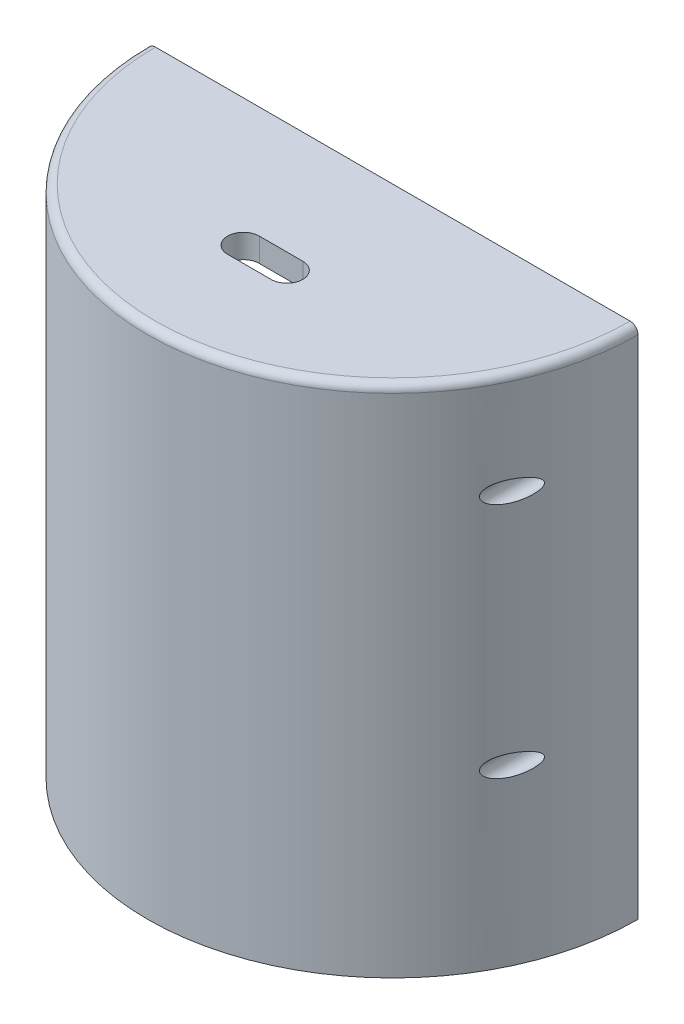
SolidWorks part; units mm, degrees
material "ABS"
ref_plane "Спереди" through (0, 0, 0) normal (0, 0, 1) x (1, 0, 0)
ref_plane "Сверху" through (0, 0, 0) normal (0, 1, 0) x (1, 0, 0)
ref_plane "Справа" through (0, 0, 0) normal (1, 0, 0) x (0, 0, -1)
sketch "Эскиз1" plane through (0, 0, 0) normal (0, 1, 0) x (1, 0, 0)
  line L0 (-31, 0) -> (-28, 0)
  line L1 (28, 0) -> (31, 0)
  arc A2 (31, 0) -> (-31, 0) centre (0, 0) cw
  arc A3 (28, 0) -> (-28, 0) centre (0, 0) cw
  dimension "D1" = 28
  dimension "D2" = 31
extrude "Бобышка-Вытянуть1" add sketch "Эскиз1" along normal blind 65
sketch "Эскиз2" plane through (0, 65, 0) normal (0, 1, 0) x (1, 0, 0)
  line L0 (-31, 0) -> (31, 0)
  arc A3 (31, 0) -> (-31, 0) centre (0, 0) cw
  arc A4 (-31, 0) -> (31, 0) centre (0, 0) ccw construction
sketch "Эскиз12" plane through (0, 0, 0) normal (0, 0, -1) x (-1, 0, 0)
  line L0 (28, 65) -> (28, 0) construction
  line L2 (28, 22) -> (28, 52) construction
  line L4 (28, 22) -> (28, 52) construction
  line L5 (28, 65) -> (28, 0) construction
  line L6 (0, 59.3805) -> (0, 0) construction
  line L7 (-28, 0) -> (28, 0) construction
  line L8 (28, 65) -> (28, 0) construction
  circle A1 centre (28, 52) radius 3
  circle A3 centre (28, 22) radius 3
  circle A4 centre (-28, 52) radius 3
  circle A5 centre (-28, 22) radius 3
  point P8 (28, 37)
  dimension "D3" = 6
  dimension "D1" = 30
  dimension "D2" = 37
extrude "Бобышка-Вытянуть5" add sketch "Эскиз12" against normal up to surface (12.6095 mm away)
sketch "Эскиз16" plane through (0, 0, 0) normal (0, 0, -1) x (-1, 0, 0)
  line L0 (0, 60.4355) -> (0, 0) construction
  circle A1 centre (28, 52) radius 1.3
  circle A3 centre (28, 22) radius 1.3
  circle A4 centre (-28, 22) radius 1.3
  circle A5 centre (-28, 52) radius 1.3
  dimension "D1" = 2.6
extrude "Вырез-Вытянуть2" cut sketch "Эскиз16" against normal through all
extrude "Бобышка-Вытянуть6" add sketch "Эскиз2" against normal blind 3
fillet "Скругление1" radius 1 1 edges at (0, 65, 31)
sketch "Эскиз18" plane through (0, 65, 0) normal (0, 1, 0) x (1, 0, 0)
  line L0 (-2.75, -16.13) -> (2.75, -16.13) construction
  line L1 (-2.75, -14.13) -> (2.75, -14.13)
  line L2 (-2.75, -18.13) -> (2.75, -18.13)
  arc A0 (-2.75, -14.13) -> (-2.75, -18.13) centre (-2.75, -16.13) ccw
  arc A1 (2.75, -18.13) -> (2.75, -14.13) centre (2.75, -16.13) ccw
  point P2 (0, -16.13)
  point P7 (0, 0)
  point P8 (0, 0)
  dimension "D2" = 2
  dimension "D1" = 16.13
  dimension "D3" = 5.5
extrude "Вырез-Вытянуть3" cut sketch "Эскиз18" against normal up to next
